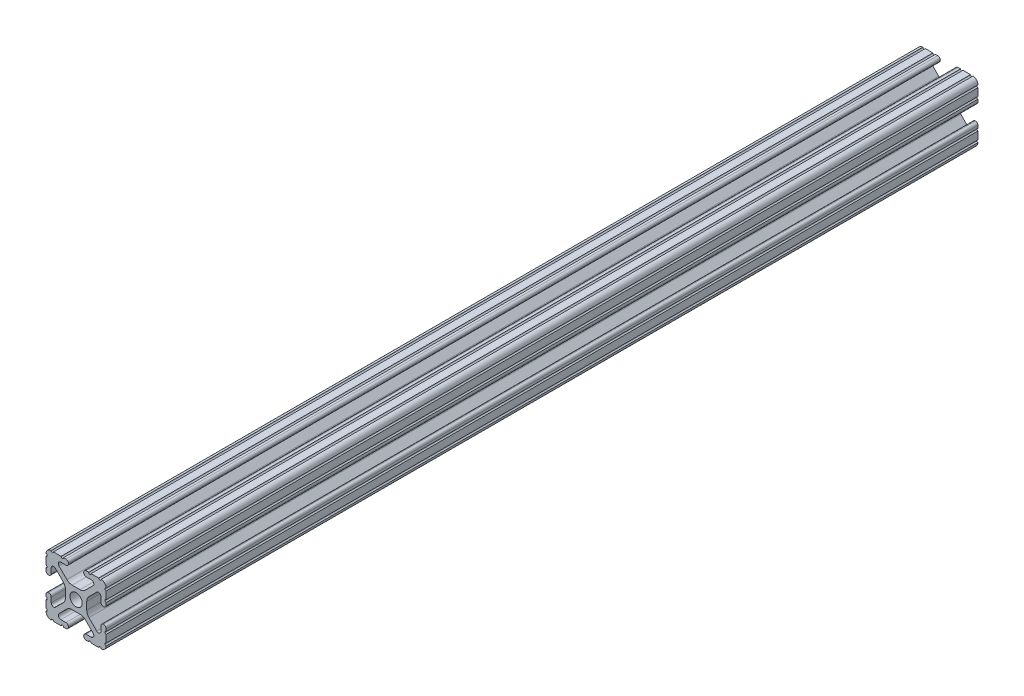
SolidWorks part; units mm, degrees
ref_plane "Front Plane" through (0, 0, 0) normal (0, 0, 1) x (1, 0, 0)
ref_plane "Top Plane" through (0, 0, 0) normal (0, 1, 0) x (1, 0, 0)
ref_plane "Right Plane" through (0, 0, 0) normal (1, 0, 0) x (0, 0, -1)
sketch "Sketch1" plane through (0, 0, 0) normal (0, 0, 1) x (1, 0, 0)
  line L88 (-7.1797, -8.6452) -> (-3.9523, -5.4237)
  line L89 (-1.7093, -4.4958) -> (1.7093, -4.4958)
  line L90 (3.9523, -5.4237) -> (7.1797, -8.6452)
  line L91 (6.4164, -10.4902) -> (4.2875, -10.4902)
  line L92 (3.2385, -11.5392) -> (3.2385, -11.651)
  line L93 (4.2875, -12.7) -> (5.3171, -12.7)
  line L94 (6.3331, -12.7) -> (9.5504, -12.7)
  line L95 (12.7, -9.5504) -> (12.7, -6.3331)
  line L96 (12.7, -5.3171) -> (12.7, -4.2875)
  line L97 (11.651, -3.2385) -> (11.5392, -3.2385)
  line L98 (10.4902, -4.2875) -> (10.4902, -6.4021)
  line L99 (8.7371, -7.1294) -> (5.441, -3.8408)
  line L100 (4.5085, -1.5932) -> (4.5085, 1.5932)
  line L101 (5.441, 3.8408) -> (8.7371, 7.1294)
  line L102 (10.4902, 6.4021) -> (10.4902, 4.2875)
  line L103 (11.5392, 3.2385) -> (11.651, 3.2385)
  line L104 (12.7, 4.2875) -> (12.7, 5.3171)
  line L105 (12.7, 6.3331) -> (12.7, 9.5504)
  line L106 (9.5504, 12.7) -> (6.3331, 12.7)
  line L107 (5.3171, 12.7) -> (4.2875, 12.7)
  line L108 (3.2385, 11.651) -> (3.2385, 11.5392)
  line L109 (4.2875, 10.4902) -> (6.4768, 10.4902)
  line L110 (7.207, 8.7244) -> (3.8983, 5.4232)
  line L111 (1.6558, 4.4958) -> (-1.6558, 4.4958)
  line L112 (-3.8983, 5.4232) -> (-7.207, 8.7244)
  line L113 (-6.4768, 10.4902) -> (-4.2875, 10.4902)
  line L114 (-3.2385, 11.5392) -> (-3.2385, 11.651)
  line L115 (-4.2875, 12.7) -> (-5.3171, 12.7)
  line L116 (-6.3331, 12.7) -> (-9.5504, 12.7)
  line L117 (-12.7, 9.5504) -> (-12.7, 6.3331)
  line L118 (-12.7, 5.3171) -> (-12.7, 4.2875)
  line L119 (-11.651, 3.2385) -> (-11.5392, 3.2385)
  line L120 (-10.4902, 4.2875) -> (-10.4902, 6.4021)
  line L121 (-8.7371, 7.1294) -> (-5.441, 3.8408)
  line L122 (-4.5085, 1.5932) -> (-4.5085, -1.5932)
  line L123 (-5.441, -3.8408) -> (-8.7371, -7.1294)
  line L124 (-10.4902, -6.4021) -> (-10.4902, -4.2875)
  line L125 (-11.5392, -3.2385) -> (-11.651, -3.2385)
  line L126 (-12.7, -4.2875) -> (-12.7, -5.3171)
  line L127 (-12.7, -6.3331) -> (-12.7, -9.5504)
  line L128 (-9.5504, -12.7) -> (-6.3331, -12.7)
  line L129 (-5.3171, -12.7) -> (-4.2875, -12.7)
  line L130 (-3.2385, -11.651) -> (-3.2385, -11.5392)
  line L131 (-4.2875, -10.4902) -> (-6.4164, -10.4902)
  circle A1 centre (0, 0) radius 2.6035
  arc A104 (-7.1797, -8.6452) -> (-6.4164, -10.4902) centre (-6.4164, -9.4098) ccw
  arc A105 (-1.7093, -4.4958) -> (-3.9523, -5.4237) centre (-1.7093, -7.6708) ccw
  arc A106 (3.9523, -5.4237) -> (1.7093, -4.4958) centre (1.7093, -7.6708) ccw
  arc A107 (6.4164, -10.4902) -> (7.1797, -8.6452) centre (6.4164, -9.4098) ccw
  arc A108 (4.2875, -10.4902) -> (3.2385, -11.5392) centre (4.2875, -11.5392) ccw
  arc A109 (3.2385, -11.651) -> (4.2875, -12.7) centre (4.2875, -11.651) ccw
  arc A110 (6.3331, -12.7) -> (5.3171, -12.7) centre (5.8251, -12.7) ccw
  arc A111 (10.5664, -12.6998) -> (9.5504, -12.7) centre (10.0584, -12.7) ccw
  arc A112 (10.5664, -12.6998) -> (12.6998, -10.5664) centre (10.5918, -10.5918) ccw
  arc A113 (12.7, -9.5504) -> (12.6998, -10.5664) centre (12.7, -10.0584) ccw
  arc A114 (12.7, -5.3171) -> (12.7, -6.3331) centre (12.7, -5.8251) ccw
  arc A115 (12.7, -4.2875) -> (11.651, -3.2385) centre (11.651, -4.2875) ccw
  arc A116 (11.5392, -3.2385) -> (10.4902, -4.2875) centre (11.5392, -4.2875) ccw
  arc A117 (8.7371, -7.1294) -> (10.4902, -6.4021) centre (9.4628, -6.4021) ccw
  arc A118 (4.5085, -1.5932) -> (5.441, -3.8408) centre (7.6835, -1.5932) ccw
  arc A119 (5.441, 3.8408) -> (4.5085, 1.5932) centre (7.6835, 1.5932) ccw
  arc A120 (10.4902, 6.4021) -> (8.7371, 7.1294) centre (9.4628, 6.4021) ccw
  arc A121 (10.4902, 4.2875) -> (11.5392, 3.2385) centre (11.5392, 4.2875) ccw
  arc A122 (11.651, 3.2385) -> (12.7, 4.2875) centre (11.651, 4.2875) ccw
  arc A123 (12.7, 6.3331) -> (12.7, 5.3171) centre (12.7, 5.8251) ccw
  arc A124 (12.6998, 10.5664) -> (12.7, 9.5504) centre (12.7, 10.0584) ccw
  arc A125 (12.6998, 10.5664) -> (10.5664, 12.6998) centre (10.5918, 10.5918) ccw
  arc A126 (9.5504, 12.7) -> (10.5664, 12.6998) centre (10.0584, 12.7) ccw
  arc A127 (5.3171, 12.7) -> (6.3331, 12.7) centre (5.8251, 12.7) ccw
  arc A128 (4.2875, 12.7) -> (3.2385, 11.651) centre (4.2875, 11.651) ccw
  arc A129 (3.2385, 11.5392) -> (4.2875, 10.4902) centre (4.2875, 11.5392) ccw
  arc A130 (7.207, 8.7244) -> (6.4768, 10.4902) centre (6.4768, 9.4563) ccw
  arc A131 (1.6558, 4.4958) -> (3.8983, 5.4232) centre (1.6558, 7.6708) ccw
  arc A132 (-3.8983, 5.4232) -> (-1.6558, 4.4958) centre (-1.6558, 7.6708) ccw
  arc A133 (-6.4768, 10.4902) -> (-7.207, 8.7244) centre (-6.4768, 9.4563) ccw
  arc A134 (-4.2875, 10.4902) -> (-3.2385, 11.5392) centre (-4.2875, 11.5392) ccw
  arc A135 (-3.2385, 11.651) -> (-4.2875, 12.7) centre (-4.2875, 11.651) ccw
  arc A136 (-6.3331, 12.7) -> (-5.3171, 12.7) centre (-5.8251, 12.7) ccw
  arc A137 (-10.5664, 12.6998) -> (-9.5504, 12.7) centre (-10.0584, 12.7) ccw
  arc A138 (-10.5664, 12.6998) -> (-12.6998, 10.5664) centre (-10.5918, 10.5918) ccw
  arc A139 (-12.7, 9.5504) -> (-12.6998, 10.5664) centre (-12.7, 10.0584) ccw
  arc A140 (-12.7, 5.3171) -> (-12.7, 6.3331) centre (-12.7, 5.8251) ccw
  arc A141 (-12.7, 4.2875) -> (-11.651, 3.2385) centre (-11.651, 4.2875) ccw
  arc A142 (-11.5392, 3.2385) -> (-10.4902, 4.2875) centre (-11.5392, 4.2875) ccw
  arc A143 (-8.7371, 7.1294) -> (-10.4902, 6.4021) centre (-9.4628, 6.4021) ccw
  arc A144 (-4.5085, 1.5932) -> (-5.441, 3.8408) centre (-7.6835, 1.5932) ccw
  arc A145 (-5.441, -3.8408) -> (-4.5085, -1.5932) centre (-7.6835, -1.5932) ccw
  arc A146 (-10.4902, -6.4021) -> (-8.7371, -7.1294) centre (-9.4628, -6.4021) ccw
  arc A147 (-10.4902, -4.2875) -> (-11.5392, -3.2385) centre (-11.5392, -4.2875) ccw
  arc A148 (-11.651, -3.2385) -> (-12.7, -4.2875) centre (-11.651, -4.2875) ccw
  arc A149 (-12.7, -6.3331) -> (-12.7, -5.3171) centre (-12.7, -5.8251) ccw
  arc A150 (-12.6998, -10.5664) -> (-12.7, -9.5504) centre (-12.7, -10.0584) ccw
  arc A151 (-12.6998, -10.5664) -> (-10.5664, -12.6998) centre (-10.5918, -10.5918) ccw
  arc A152 (-9.5504, -12.7) -> (-10.5664, -12.6998) centre (-10.0584, -12.7) ccw
  arc A153 (-5.3171, -12.7) -> (-6.3331, -12.7) centre (-5.8251, -12.7) ccw
  arc A154 (-4.2875, -12.7) -> (-3.2385, -11.651) centre (-4.2875, -11.651) ccw
  arc A155 (-3.2385, -11.5392) -> (-4.2875, -10.4902) centre (-4.2875, -11.5392) ccw
extrude "Boss-Extrude1" add sketch "Sketch1" along normal mid plane 368.3
